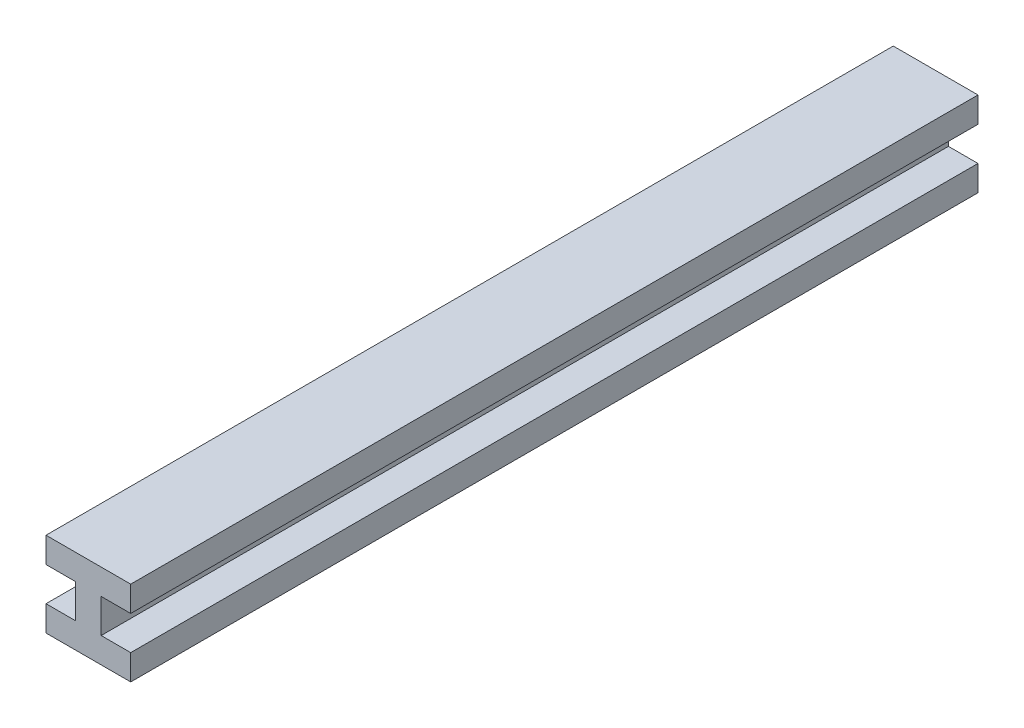
SolidWorks part; units mm, degrees
ref_plane "Front Plane" through (0, 0, 0) normal (0, 0, 1) x (1, 0, 0)
ref_plane "Top Plane" through (0, 0, 0) normal (0, 1, 0) x (1, 0, 0)
ref_plane "Right Plane" through (0, 0, 0) normal (1, 0, 0) x (0, 0, -1)
sketch "Sketch1" plane through (0, 0, 0) normal (0, 0, 1) x (1, 0, 0)
  line L0 (0, -120.0631) -> (0, 0) construction
  line L1 (5, 0) -> (-5, 0)
  line L2 (-5, 0) -> (-5, 3)
  line L3 (-5, 3) -> (-1.5108, 3)
  line L4 (-1.5108, 3) -> (-1.5108, 7)
  line L5 (-1.5108, 7) -> (-5, 7)
  line L6 (-5, 7) -> (-5, 10)
  line L7 (-5, 10) -> (5, 10)
  line L9 (5, 7) -> (5, 10)
  line L10 (1.5108, 7) -> (5, 7)
  line L11 (1.5108, 3) -> (1.5108, 7)
  line L12 (5, 3) -> (1.5108, 3)
  line L13 (5, 0) -> (5, 3)
  line L14 (0, 10) -> (0, 5883.0897) construction
  dimension "D2" = 3
  dimension "D3" = 3
extrude "Boss-Extrude1" add sketch "Sketch1" along normal blind 100
